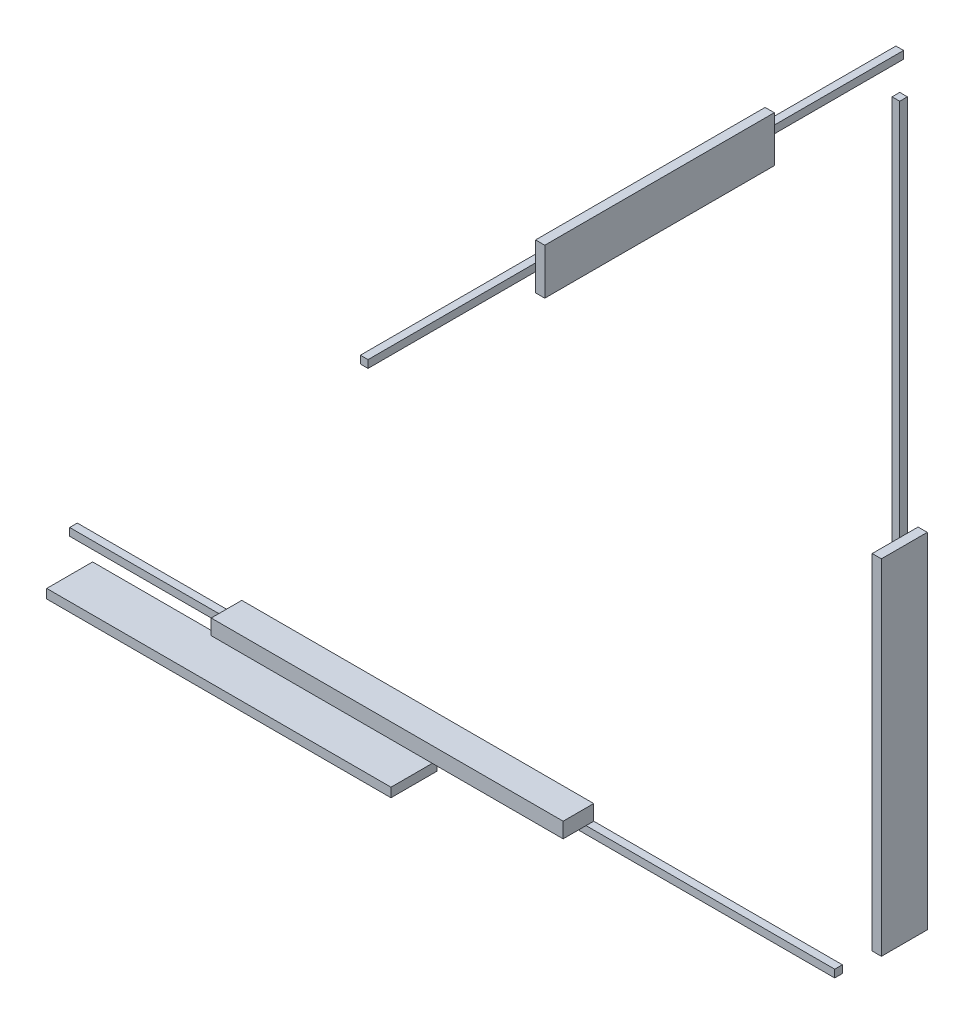
SolidWorks part; units mm, degrees
ref_plane "前视基准面" through (0, 0, 0) normal (0, 0, 1) x (1, 0, 0)
ref_plane "上视基准面" through (0, 0, 0) normal (0, 1, 0) x (1, 0, 0)
ref_plane "右视基准面" through (0, 0, 0) normal (1, 0, 0) x (0, 0, -1)
other "Configuration Table"
sketch "草图1" plane through (0, 0, 0) normal (0, 0, 1) x (1, 0, 0)
  line L1 (-50, -58.5) -> (50, -58.5)
  line L2 (-50, -58.5) -> (-50, -57.5)
  line L3 (-50, -57.5) -> (50, -57.5)
  line L4 (50, -58.5) -> (50, -57.5)
  line L5 (-50, -58.5) -> (50, -57.5) construction
  line L6 (-50, -57.5) -> (50, -58.5) construction
  point P0 (0, -58)
extrude "overall X dimension marker - body length 100 mm" add sketch "草图1" along normal blind 1 from offset 0.5 separate body
sketch "草图2" plane through (0, 0, 0) normal (0, 0, 1) x (1, 0, 0)
  line L1 (57.5, -45) -> (58.5, -45)
  line L2 (57.5, -45) -> (57.5, 45)
  line L3 (57.5, 45) -> (58.5, 45)
  line L4 (58.5, -45) -> (58.5, 45)
  line L5 (57.5, -45) -> (58.5, 45) construction
  line L6 (57.5, 45) -> (58.5, -45) construction
  point P0 (58, 0)
extrude "overall Y dimension marker - body width 90 mm" add sketch "草图2" along normal blind 1 from offset 0.5 separate body
sketch "草图3" plane through (0, 0, 0) normal (0, 0, 1) x (1, 0, 0)
  line L1 (57.5, 49.5) -> (58.5, 49.5)
  line L2 (57.5, 49.5) -> (57.5, 50.5)
  line L3 (57.5, 50.5) -> (58.5, 50.5)
  line L4 (58.5, 49.5) -> (58.5, 50.5)
  line L5 (57.5, 49.5) -> (58.5, 50.5) construction
  line L6 (57.5, 50.5) -> (58.5, 49.5) construction
  point P0 (58, 50)
extrude "overall Z dimension marker - body height 70 mm" add sketch "草图3" along normal blind 70 separate body
sketch "草图4" plane through (0, 0, 0) normal (0, 0, 1) x (1, 0, 0)
  line L1 (-23, -52) -> (23, -52)
  line L2 (-23, -52) -> (-23, -50)
  line L3 (-23, -50) -> (23, -50)
  line L4 (23, -52) -> (23, -50)
  line L5 (-23, -52) -> (23, -50) construction
  line L6 (-23, -50) -> (23, -52) construction
  point P0 (0, -51)
extrude "front arrow / sensor face marker" add sketch "草图4" along normal blind 4 from offset 5 separate body
sketch "草图5" plane through (0, 0, 0) normal (0, 0, 1) x (1, 0, 0)
  line L1 (-47.5, -61.6) -> (-2.5, -61.6)
  line L2 (-47.5, -61.6) -> (-47.5, -60.4)
  line L3 (-47.5, -60.4) -> (-2.5, -60.4)
  line L4 (-2.5, -61.6) -> (-2.5, -60.4)
  line L5 (-47.5, -61.6) -> (-2.5, -60.4) construction
  line L6 (-47.5, -60.4) -> (-2.5, -61.6) construction
  point P0 (-25, -61)
extrude "overall label plate - 100mm" add sketch "草图5" along normal blind 6 separate body
sketch "草图6" plane through (0, 0, 0) normal (0, 0, 1) x (1, 0, 0)
  line L1 (60.4, -47.5) -> (61.6, -47.5)
  line L2 (60.4, -47.5) -> (60.4, -2.5)
  line L3 (60.4, -2.5) -> (61.6, -2.5)
  line L4 (61.6, -47.5) -> (61.6, -2.5)
  line L5 (60.4, -47.5) -> (61.6, -2.5) construction
  line L6 (60.4, -2.5) -> (61.6, -47.5) construction
  point P0 (61, -25)
extrude "overall label plate - 90mm" add sketch "草图6" along normal blind 6 separate body
sketch "草图7" plane through (0, 0, 0) normal (0, 0, 1) x (1, 0, 0)
  line L1 (60.4, 49) -> (61.6, 49)
  line L2 (60.4, 49) -> (60.4, 55)
  line L3 (60.4, 55) -> (61.6, 55)
  line L4 (61.6, 49) -> (61.6, 55)
  line L5 (60.4, 49) -> (61.6, 55) construction
  line L6 (60.4, 55) -> (61.6, 49) construction
  point P0 (61, 52)
extrude "overall label plate - 70mm" add sketch "草图7" along normal blind 30 from offset 20 separate body
